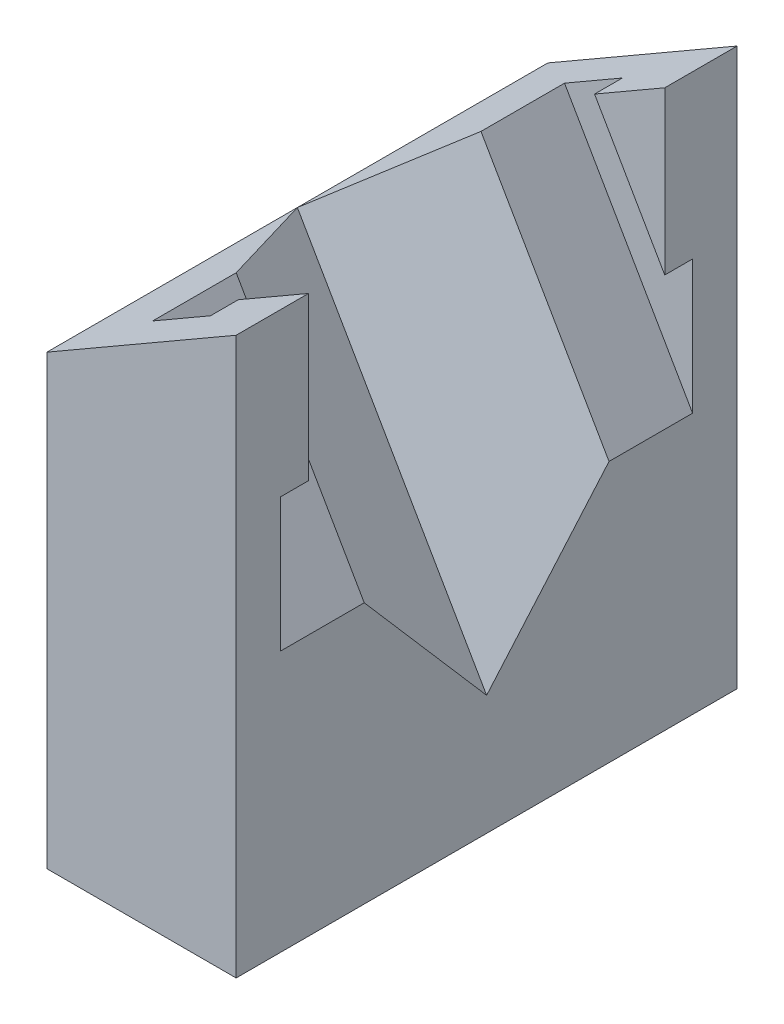
SolidWorks part; units mm, degrees
ref_plane "Front Plane" through (0, 0, 0) normal (0, 0, 1) x (1, 0, 0)
ref_plane "Top Plane" through (0, 0, 0) normal (0, 1, 0) x (1, 0, 0)
ref_plane "Right Plane" through (0, 0, 0) normal (1, 0, 0) x (0, 0, -1)
sketch "Sketch1" plane through (0, 0, 0) normal (0, 1, 0) x (1, 0, 0)
  line L1 (8.5, -22.5) -> (-8.5, -22.5)
  line L2 (8.5, -22.5) -> (8.5, 22.5)
  line L3 (8.5, 22.5) -> (-8.5, 22.5)
  line L4 (-8.5, -22.5) -> (-8.5, 22.5)
  line L5 (8.5, -22.5) -> (-8.5, 22.5) construction
  line L6 (8.5, 22.5) -> (-8.5, -22.5) construction
  point P0 (0, 0)
  dimension "D1" = 45
  dimension "D2" = 17
extrude "Boss-Extrude1" add sketch "Sketch1" along normal blind 50
sketch "Sketch2" plane through (0, 0, 22.5) normal (0, 0, 1) x (1, 0, 0)
  line L0 (8.5, 50) -> (-8.5, 40.185)
  line L1 (-8.5, 50) -> (-8.5, 0) construction
  line L2 (-8.5, 40.185) -> (-8.5, 50)
  line L3 (-8.5, 50) -> (8.5, 50) construction
  line L4 (-8.5, 50) -> (8.5, 50)
  dimension "D1" = 30
extrude "Cut-Extrude1" cut sketch "Sketch2" against normal through all
sketch "Sketch3" plane through (-19.5256, 33.8194, 0) normal (-0.5, 0.866, 0) x (0.866, 0.5, 0)
  line L0 (12.7313, 0) -> (32.3612, 0) construction
  line L1 (12.7313, 22.5) -> (12.7313, -22.5) construction
  line L2 (32.3612, -22.5) -> (32.3612, 22.5) construction
  line L19 (25.0789, -18.5) -> (19.0789, -18.5)
  line L20 (49.6817, 0) -> (40.4441, 16)
  line L21 (40.4441, 16) -> (25.0789, 16)
  line L22 (19.0789, 10.9944) -> (12.7313, 0)
  line L23 (12.7313, 0) -> (19.0789, -10.9944)
  line L24 (25.0789, -16) -> (40.4441, -16)
  line L25 (40.4441, -16) -> (49.6817, 0)
  line L26 (19.0789, -18.5) -> (19.0789, -10.9944)
  line L27 (25.0789, -18.5) -> (25.0789, -16)
  line L28 (12.7313, -22.5) -> (32.3612, -22.5) construction
  line L29 (25.0789, 18.5) -> (25.0789, 16)
  line L30 (25.0789, 18.5) -> (19.0789, 18.5)
  line L31 (19.0789, 18.5) -> (19.0789, 10.9944)
  line L32 (21.9689, 16) -> (19.0789, 10.9944) construction
  line L33 (25.0789, 16) -> (21.9689, 16) construction
  line L34 (19.0789, -10.9944) -> (21.9689, -16) construction
  line L35 (21.9689, -16) -> (25.0789, -16) construction
  circle A0 centre (31.2065, 0) radius 16 construction
  point P20 (0, 0)
  dimension "D1" = 32
  dimension "D2" = 2.89
  dimension "D3" = 6
  dimension "D4" = 4
extrude "Cut-Extrude3" cut sketch "Sketch3" against normal through all
